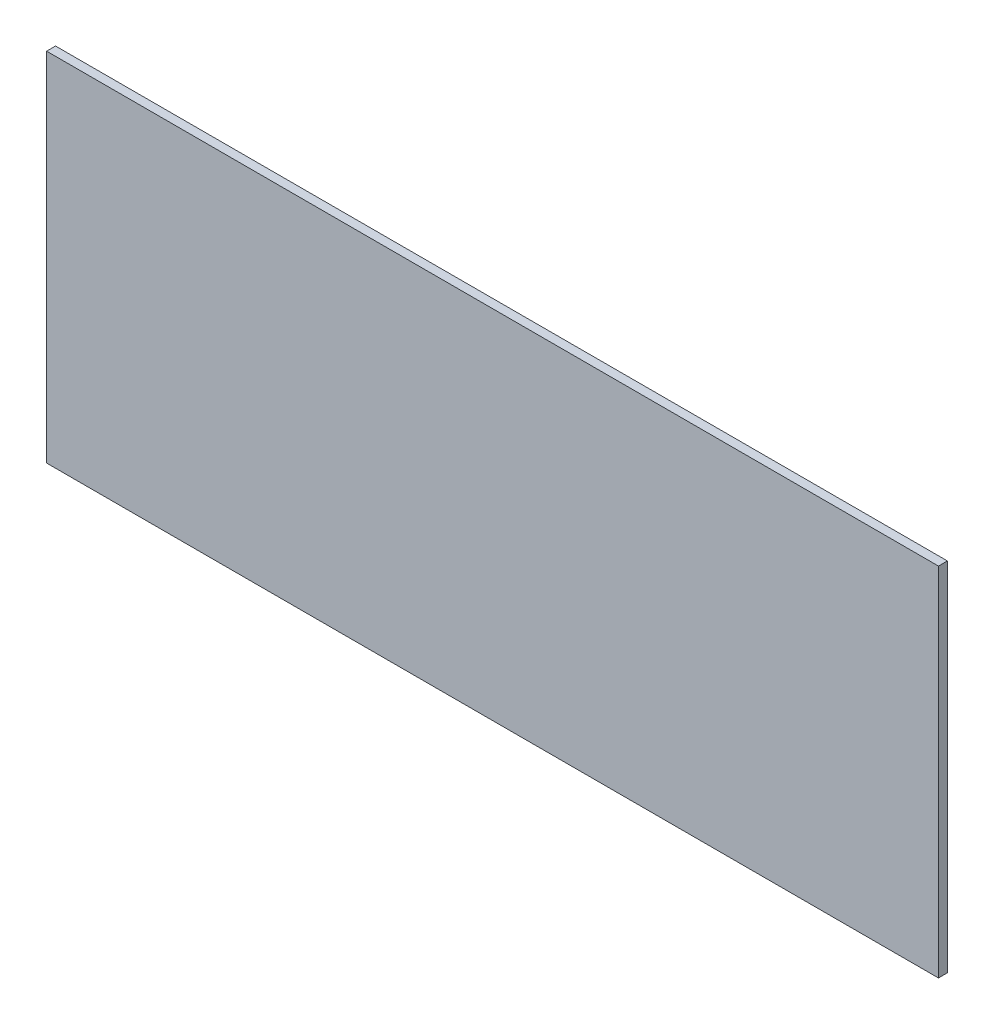
SolidWorks part; units mm, degrees
ref_plane "Front Plane" through (0, 0, 0) normal (0, 0, 1) x (1, 0, 0)
ref_plane "Top Plane" through (0, 0, 0) normal (0, 1, 0) x (1, 0, 0)
ref_plane "Right Plane" through (0, 0, 0) normal (1, 0, 0) x (0, 0, -1)
sketch "Sketch1" plane through (0, 0, 0) normal (0, 0, 1) x (1, 0, 0)
  line L1 (0, 0) -> (254, 0)
  line L2 (0, 0) -> (0, 101.6)
  line L3 (0, 101.6) -> (254, 101.6)
  line L4 (254, 0) -> (254, 101.6)
  dimension "D1" = 254
  dimension "D2" = 101.6
extrude "Boss-Extrude1" add sketch "Sketch1" along normal blind 2.54
